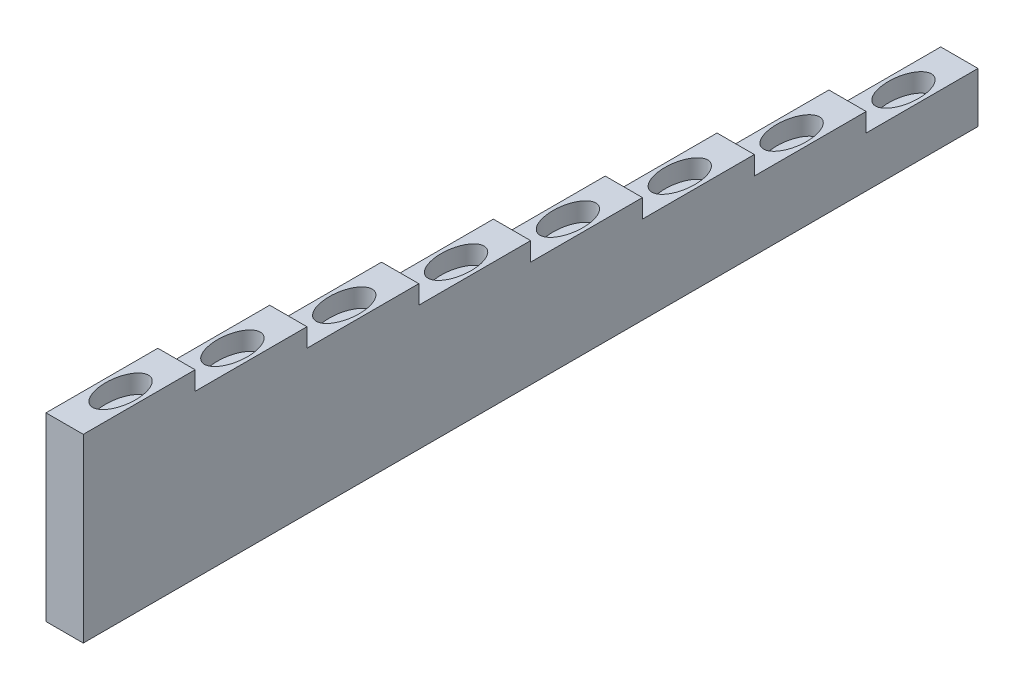
SolidWorks part; units mm, degrees
ref_plane "Front Plane" through (0, 0, 0) normal (0, 0, 1) x (1, 0, 0)
ref_plane "Top Plane" through (0, 0, 0) normal (0, 1, 0) x (1, 0, 0)
ref_plane "Right Plane" through (0, 0, 0) normal (1, 0, 0) x (0, 0, -1)
sketch "Sketch2" plane through (0, 0, 0) normal (0, 0, 1) x (1, 0, 0)
  line L0 (0, 0) -> (0, -20.3) construction
  line L1 (0, -20.3) -> (-7.23, -20.3) construction
  line L2 (-7.23, -20.3) -> (-7.23, -34)
  line L3 (-7.23, -34) -> (-9.23, -34)
  line L4 (-9.23, -34) -> (-9.23, -2)
  line L5 (-9.23, -2) -> (-7.23, -2)
  line L6 (-7.23, -2) -> (-7.23, -20.3)
  point P10 (-7.23, -20.3)
  dimension "D1" = 18.3
  dimension "D2" = 13.7
extrude "Boss-Extrude1" add sketch "Sketch2" along normal blind 48
sketch "Sketch7" plane through (-7.23, 0, 0) normal (1, 0, 0) x (0, 0, -1)
  line L0 (0, -20.3) -> (-48, -20.3) construction
  line L1 (-48, -34) -> (-48, -2) construction
  line L2 (-48, -16.3) -> (-48, -24.3)
  line L3 (-48, -24.3) -> (-42, -24.3)
  line L4 (-42, -24.3) -> (-42, -25.3)
  line L5 (-42, -25.3) -> (-36, -25.3)
  line L6 (-36, -25.3) -> (-36, -26.3)
  line L7 (-36, -26.3) -> (-30, -26.3)
  line L8 (-30, -26.3) -> (-30, -27.3)
  line L9 (-30, -27.3) -> (-24, -27.3)
  line L10 (-24, -27.3) -> (-24, -28.3)
  line L11 (-24, -28.3) -> (-18, -28.3)
  line L12 (-18, -28.3) -> (-18, -29.3)
  line L13 (-18, -29.3) -> (-12, -29.3)
  line L14 (-12, -29.3) -> (-12, -30.3)
  line L15 (-12, -30.3) -> (-6, -30.3)
  line L16 (-6, -30.3) -> (-6, -31.3)
  line L17 (-6, -31.3) -> (0, -31.3)
  line L18 (0, -34) -> (0, -2) construction
  line L19 (0, -31.3) -> (0, -9.3)
  line L21 (-48, -16.3) -> (-42, -16.3)
  line L22 (-6, -9.3) -> (0, -9.3)
  line L23 (-6, -10.3) -> (-6, -9.3)
  line L24 (-12, -10.3) -> (-6, -10.3)
  line L25 (-12, -11.3) -> (-12, -10.3)
  line L26 (-18, -11.3) -> (-12, -11.3)
  line L27 (-18, -12.3) -> (-18, -11.3)
  line L28 (-24, -12.3) -> (-18, -12.3)
  line L29 (-24, -13.3) -> (-24, -12.3)
  line L30 (-30, -13.3) -> (-24, -13.3)
  line L31 (-30, -14.3) -> (-30, -13.3)
  line L32 (-36, -14.3) -> (-30, -14.3)
  line L33 (-36, -15.3) -> (-36, -14.3)
  line L34 (-42, -15.3) -> (-36, -15.3)
  line L35 (-42, -16.3) -> (-42, -15.3)
  dimension "D1" = 8
extrude "Cut-Extrude4" cut sketch "Sketch7" against normal blind 2
sketch "Sketch8" plane through (0, -24.3, 0) normal (0, 1, 0) x (1, 0, 0)
  line L0 (-8.23, -48) -> (-8.23, -42) construction
  line L1 (-9.23, -48) -> (-7.23, -48) construction
  line L2 (-9.23, -42) -> (-7.23, -42) construction
  ellipse E0 centre (-8.23, -45) end of major axis (-8.23, -43.5) minor radius 0.8
extrude "Cut-Extrude6" cut sketch "Sketch8" against normal blind 1 and the other way blind 9 contours E0
sketch "Sketch13" plane through (0, -25.3, 0) normal (0, 1, 0) x (1, 0, 0)
  line L0 (-8.23, -42) -> (-8.23, -36)
  line L1 (-9.23, -42) -> (-7.23, -42) construction
  line L2 (-9.23, -36) -> (-7.23, -36) construction
  ellipse E0 centre (-8.23, -39) end of major axis (-8.23, -37.5) minor radius 0.8
sketch "Sketch14" plane through (0, -26.3, 0) normal (0, 1, 0) x (1, 0, 0)
  line L0 (-8.23, -36) -> (-8.23, -30)
  line L1 (-9.23, -36) -> (-7.23, -36) construction
  line L2 (-9.23, -30) -> (-7.23, -30) construction
  ellipse E0 centre (-8.23, -33) end of major axis (-8.23, -31.5) minor radius 0.8
sketch "Sketch15" plane through (0, -27.3, 0) normal (0, 1, 0) x (1, 0, 0)
  line L0 (-8.23, -30) -> (-8.23, -24)
  line L1 (-9.23, -30) -> (-7.23, -30) construction
  line L2 (-9.23, -24) -> (-7.23, -24) construction
  ellipse E0 centre (-8.23, -27) end of major axis (-8.23, -25.5) minor radius 0.8
sketch "Sketch16" plane through (0, -28.3, 0) normal (0, 1, 0) x (1, 0, 0)
  line L0 (-8.23, -24) -> (-8.23, -18)
  line L1 (-9.23, -24) -> (-7.23, -24) construction
  line L2 (-9.23, -18) -> (-7.23, -18) construction
  ellipse E0 centre (-8.23, -21) end of major axis (-8.23, -19.5) minor radius 0.8
sketch "Sketch17" plane through (0, -29.3, 0) normal (0, 1, 0) x (1, 0, 0)
  line L0 (-8.23, -18) -> (-8.23, -12)
  line L1 (-9.23, -18) -> (-7.23, -18) construction
  line L2 (-9.23, -12) -> (-7.23, -12) construction
  ellipse E0 centre (-8.23, -15) end of major axis (-8.23, -13.5) minor radius 0.8
sketch "Sketch18" plane through (0, -30.3, 0) normal (0, 1, 0) x (1, 0, 0)
  line L0 (-8.23, -12) -> (-8.23, -6)
  line L1 (-9.23, -12) -> (-7.23, -12) construction
  line L2 (-9.23, -6) -> (-7.23, -6) construction
  ellipse E0 centre (-8.23, -9) end of major axis (-8.23, -7.5) minor radius 0.8
sketch "Sketch19" plane through (0, -31.3, 0) normal (0, 1, 0) x (1, 0, 0)
  line L0 (-8.23, -6) -> (-8.23, 0)
  line L1 (-9.23, -6) -> (-7.23, -6) construction
  line L2 (-9.23, 0) -> (-7.23, 0) construction
  ellipse E0 centre (-8.23, -3) end of major axis (-8.23, -1.5) minor radius 0.8
extrude "Cut-Extrude7" cut sketch "Sketch13" against normal blind 1 and the other way blind 11 contours E0
extrude "Cut-Extrude8" cut sketch "Sketch14" against normal blind 1 and the other way blind 13 contours E0
extrude "Cut-Extrude9" cut sketch "Sketch15" against normal blind 1 and the other way blind 15 contours E0
extrude "Cut-Extrude10" cut sketch "Sketch16" against normal blind 1 and the other way blind 17 contours E0
extrude "Cut-Extrude11" cut sketch "Sketch17" against normal blind 1 and the other way blind 19 contours E0
extrude "Cut-Extrude12" cut sketch "Sketch18" against normal blind 1 and the other way blind 21 contours E0
extrude "Cut-Extrude13" cut sketch "Sketch19" against normal blind 1 and the other way blind 23 contours E0
sketch "Sketch20" plane through (0, 0, 0) normal (1, 0, 0) x (0, 0, -1)
  line L1 (-53.1278, -21.8176) -> (8.2797, -21.8176)
  line L2 (-53.1278, -21.8176) -> (-53.1278, 0.5499)
  line L3 (-53.1278, 0.5499) -> (8.2797, 0.5499)
  line L4 (8.2797, -21.8176) -> (8.2797, 0.5499)
extrude "Cut-Extrude14" cut sketch "Sketch20" against normal blind 10
